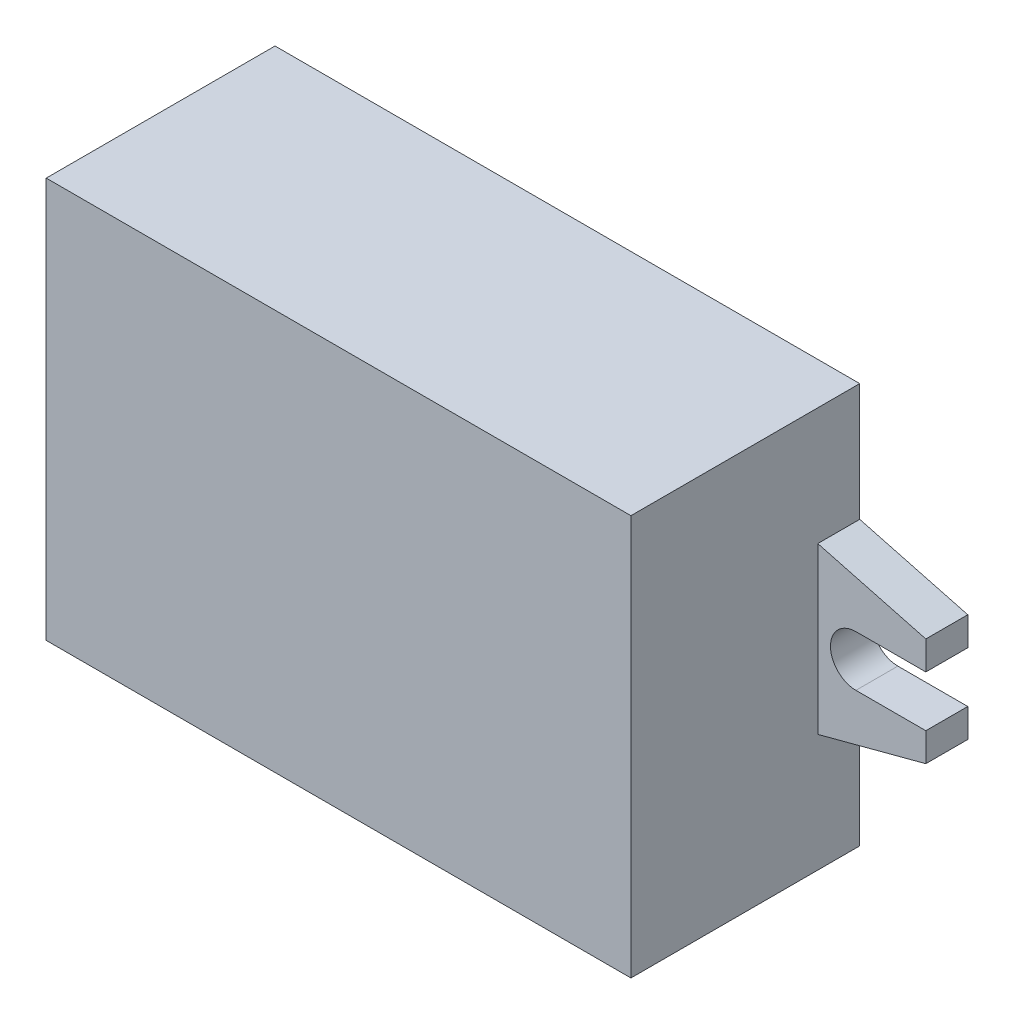
SolidWorks part; units mm, degrees
ref_plane "前视基准面" through (0, 0, 0) normal (0, 0, 1) x (1, 0, 0)
ref_plane "上视基准面" through (0, 0, 0) normal (0, 1, 0) x (1, 0, 0)
ref_plane "右视基准面" through (0, 0, 0) normal (1, 0, 0) x (0, 0, -1)
sketch "草图1" plane through (0, 0, 0) normal (0, 0, 1) x (1, 0, 0)
  line L1 (0, 0) -> (46, 0)
  line L2 (0, 0) -> (0, 31.5)
  line L3 (0, 31.5) -> (46, 31.5)
  line L4 (46, 0) -> (46, 31.5)
  dimension "D1" = 46
  dimension "D2" = 31.5
extrude "凸台-拉伸1" add sketch "草图1" along normal blind 18
sketch "草图3" plane through (0, 0, 0) normal (-1, 0, 0) x (0, 0, 1)
  line L0 (0, 31.5) -> (0, 0) construction
  line L1 (0, 9.25) -> (3.3, 9.25)
  line L2 (0, 9.25) -> (0, 22.25)
  line L3 (0, 22.25) -> (3.3, 22.25)
  line L4 (3.3, 9.25) -> (3.3, 22.25)
  line L5 (18, 0) -> (0, 0) construction
  dimension "D1" = 3.3
  dimension "D2" = 13
  dimension "D3" = 9.25
extrude "凸台-拉伸2" add sketch "草图3" along normal blind 8.5
sketch "草图4" plane through (46, 0, 0) normal (1, 0, 0) x (0, 0, -1)
  line L0 (0, 0) -> (0, 31.5) construction
  line L1 (0, 9.25) -> (-3.3, 9.25)
  line L2 (0, 9.25) -> (0, 22.25)
  line L3 (0, 22.25) -> (-3.3, 22.25)
  line L4 (-3.3, 9.25) -> (-3.3, 22.25)
  line L5 (-18, 0) -> (0, 0) construction
  dimension "D1" = 3.3
  dimension "D2" = 13
  dimension "D3" = 9.25
extrude "凸台-拉伸3" add sketch "草图4" along normal blind 8.5
sketch "草图5" plane through (0, 0, 3.3) normal (0, 0, 1) x (1, 0, 0)
  line L0 (-8.5, 22.25) -> (-8.5, 20)
  line L1 (-8.5, 9.25) -> (-8.5, 22.25) construction
  line L2 (-8.5, 20) -> (0, 22.25)
  line L3 (0, 22.25) -> (-8.5, 22.25)
  line L4 (-8.5, 11.5) -> (0, 9.25)
  line L5 (0, 9.25) -> (-8.5, 9.25)
  line L6 (-8.5, 9.25) -> (-8.5, 11.5)
  line L7 (0, 31.5) -> (0, 0) construction
  line L8 (-3, 17.75) -> (-8.5, 17.75)
  line L9 (-3, 13.75) -> (-8.5, 13.75)
  line L10 (-8.5, 17.75) -> (-8.5, 13.75)
  arc A0 (-3, 13.75) -> (-3, 17.75) centre (-3, 15.75) ccw
  dimension "D3" = 4
  dimension "D1" = 2.25
  dimension "D2" = 2.25
  dimension "D4" = 3
  dimension "D5" = 6.5
extrude "切除-拉伸1" cut sketch "草图5" against normal through all
sketch "草图6" plane through (0, 0, 3.3) normal (0, 0, 1) x (1, 0, 0)
  line L0 (46, 22.25) -> (54.5, 20)
  line L1 (54.5, 22.25) -> (54.5, 9.25) construction
  line L2 (54.5, 20) -> (54.5, 22.25)
  line L3 (54.5, 22.25) -> (46, 22.25)
  line L4 (46, 9.25) -> (54.5, 9.25)
  line L5 (54.5, 9.25) -> (54.5, 11.5)
  line L6 (54.5, 11.5) -> (46, 9.25)
  line L7 (46, 22.25) -> (46, 9.25) construction
  line L8 (49, 17.75) -> (54.5, 17.75)
  line L9 (54.5, 17.75) -> (54.5, 13.75)
  line L10 (54.5, 13.75) -> (49, 13.75)
  arc A0 (49, 17.75) -> (49, 13.75) centre (49, 15.75) ccw
  dimension "D3" = 4
  dimension "D1" = 2.25
  dimension "D2" = 2.25
  dimension "D4" = 3
  dimension "D5" = 6.5
extrude "切除-拉伸2" cut sketch "草图6" against normal through all
